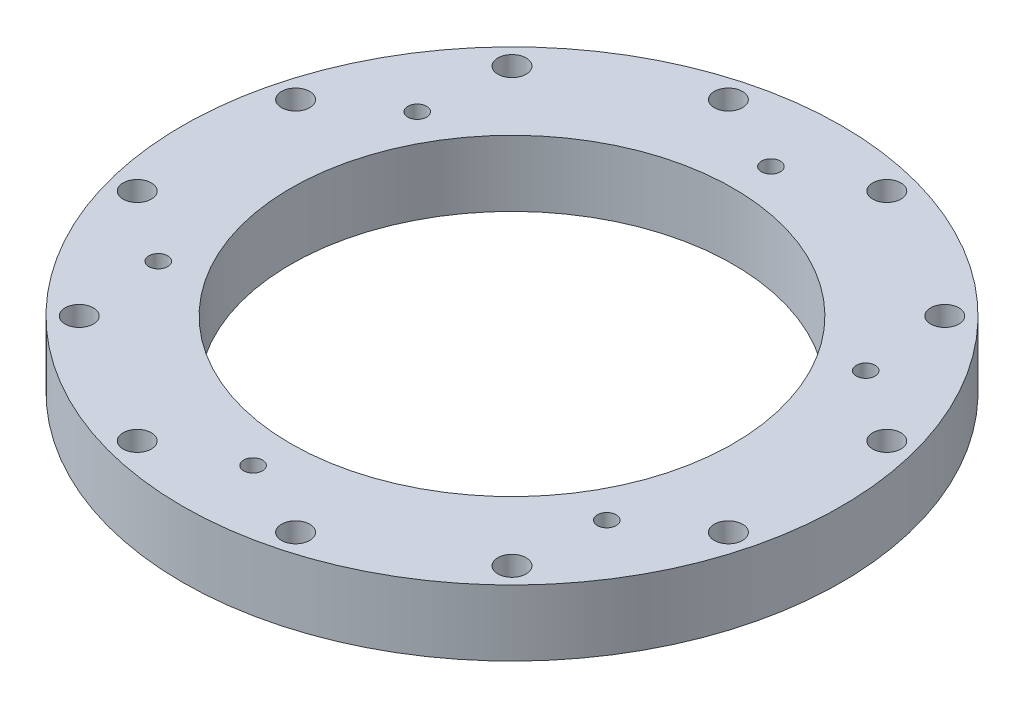
SolidWorks part; units mm, degrees
ref_plane "Front Plane" through (0, 0, 0) normal (0, 0, 1) x (1, 0, 0)
ref_plane "Top Plane" through (0, 0, 0) normal (0, 1, 0) x (1, 0, 0)
ref_plane "Right Plane" through (0, 0, 0) normal (1, 0, 0) x (0, 0, -1)
sketch "Sketch1" plane through (0, 0, 0) normal (0, 1, 0) x (1, 0, 0)
  line L0 (-53.2191, 0) -> (0, 0) construction
  line L1 (0, 0) -> (-55.1529, -14.7782) construction
  circle A0 centre (0, 0) radius 35
  circle A1 centre (0, 0) radius 27.5 construction
  circle A2 centre (0, 0) radius 23.5
  circle A3 centre (0, 27.5) radius 1
  circle A4 centre (23.8157, 13.75) radius 1
  circle A5 centre (23.8157, -13.75) radius 1
  circle A6 centre (0, -27.5) radius 1
  circle A7 centre (-23.8157, -13.75) radius 1
  circle A8 centre (-23.8157, 13.75) radius 1
  circle A9 centre (0, 0) radius 32.5 construction
  circle A10 centre (-31.3926, -8.4116) radius 1.5
  circle A11 centre (-31.3926, 8.4116) radius 1.5
  circle A12 centre (-22.981, 22.981) radius 1.5
  circle A13 centre (-8.4116, 31.3926) radius 1.5
  circle A14 centre (8.4116, 31.3926) radius 1.5
  circle A15 centre (22.981, 22.981) radius 1.5
  circle A16 centre (31.3926, 8.4116) radius 1.5
  circle A17 centre (31.3926, -8.4116) radius 1.5
  circle A18 centre (22.981, -22.981) radius 1.5
  circle A19 centre (8.4116, -31.3926) radius 1.5
  circle A20 centre (-8.4116, -31.3926) radius 1.5
  circle A21 centre (-22.981, -22.981) radius 1.5
  point P19 (0, 0)
  point P47 (0, 0)
  dimension "D1" = 70
  dimension "D2" = 47
  dimension "D3" = 55
  dimension "D4" = 2
  dimension "D7" = 65
  dimension "D8" = 3
  dimension "D6" = 15
  dimension "D5" = 6
  dimension "D9" = 12
extrude "Boss-Extrude1" add sketch "Sketch1" along normal blind 7
